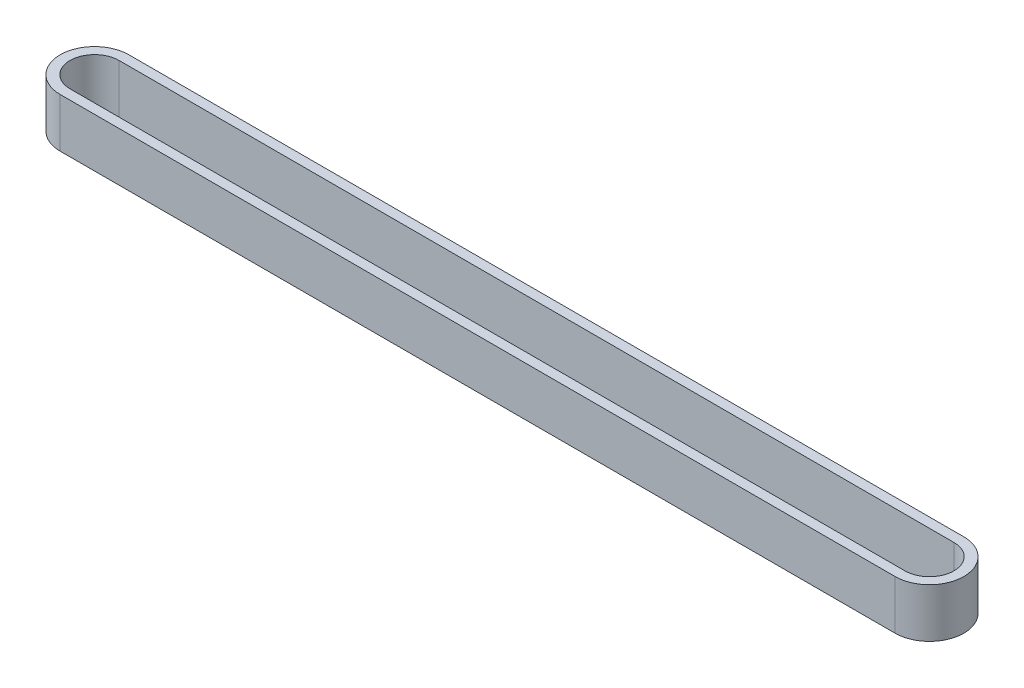
SolidWorks part; units mm, degrees
material "天然橡胶"
ref_plane "前视基准面" through (0, 0, 0) normal (0, 0, 1) x (1, 0, 0)
ref_plane "上视基准面" through (0, 0, 0) normal (0, 1, 0) x (1, 0, 0)
ref_plane "右视基准面" through (0, 0, 0) normal (1, 0, 0) x (0, 0, -1)
other "Configuration Table"
sketch "草图1" plane through (0, 0, 0) normal (0, 1, 0) x (1, 0, 0)
  line L0 (0, 0) -> (-170, 0) construction
  line L1 (0, -5) -> (-170, -5)
  line L2 (0, 5) -> (-170, 5)
  line L3 (0, 0) -> (-170, 0) construction
  line L4 (0, -7) -> (-170, -7)
  line L5 (0, 7) -> (-170, 7)
  arc A0 (0, -5) -> (0, 5) centre (0, 0) ccw
  arc A1 (-170, 5) -> (-170, -5) centre (-170, 0) ccw
  arc A2 (0, -7) -> (0, 7) centre (0, 0) ccw
  arc A3 (-170, 7) -> (-170, -7) centre (-170, 0) ccw
  point P3 (-85, 0)
  point P8 (-85, 0)
  dimension "D3" = 5
  dimension "D1" = 170
  dimension "D2" = 2
extrude "凸台-拉伸1" add sketch "草图1" along normal blind 10
